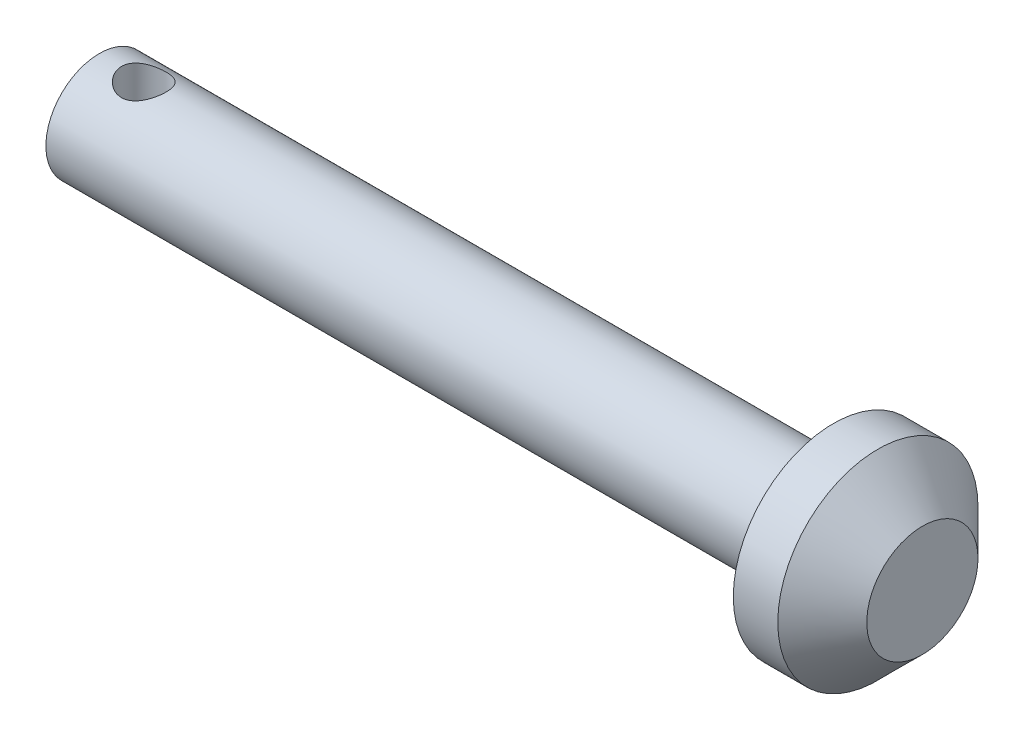
SolidWorks part; units mm, degrees
ref_plane "Płaszczyzna przednia" through (0, 0, 0) normal (0, 0, 1) x (1, 0, 0)
ref_plane "Płaszczyzna górna" through (0, 0, 0) normal (0, 1, 0) x (1, 0, 0)
ref_plane "Płaszczyzna prawa" through (0, 0, 0) normal (1, 0, 0) x (0, 0, -1)
sketch "Szkic1" plane through (0, 0, 0) normal (1, 0, 0) x (0, 0, -1)
  circle A0 centre (0, 0) radius 2.4
  dimension "D1" = 4.8
extrude "Dodanie-wyciągnięcie1" add sketch "Szkic1" along normal blind 5 and the other way blind 28
sketch "Szkic2" plane through (5, 0, 0) normal (1, 0, 0) x (0, 0, -1)
  circle A0 centre (0, 0) radius 4.5
  dimension "D1" = 9
extrude "Dodanie-wyciągnięcie2" add sketch "Szkic2" along normal blind 4
chamfer "Sfazowanie1" distance 2 angle 45 1 edges at (9, 0, -4.5)
sketch "Szkic3" plane through (0, 0, 0) normal (0, 1, 0) x (1, 0, 0)
  line L0 (0, 0) -> (-26, 0) construction
  circle A0 centre (-26, 0) radius 1
  dimension "D1" = 2
  dimension "D2" = 26
extrude "Wytnij-wyciągnięcie1" cut sketch "Szkic3" against normal through all both and the other way through all
